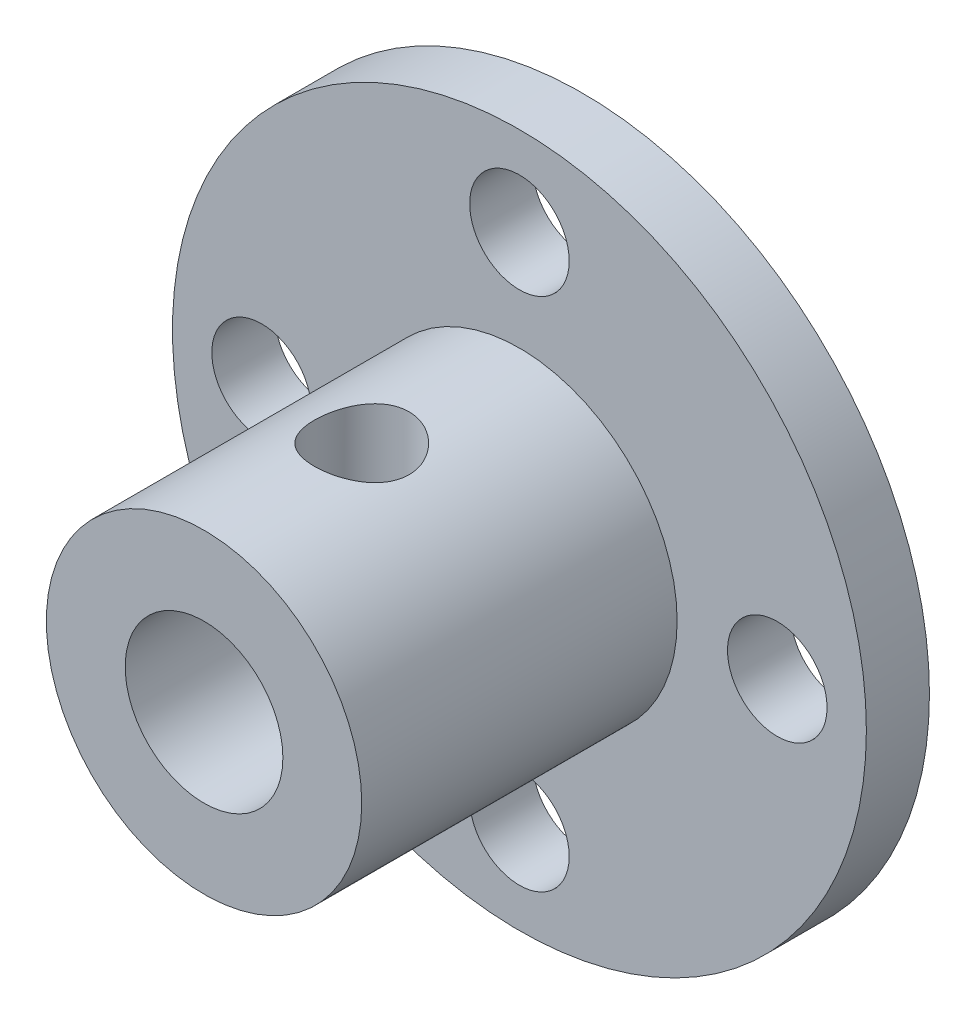
SolidWorks part; units mm, degrees
ref_plane "Front Plane" through (0, 0, 0) normal (0, 0, 1) x (1, 0, 0)
ref_plane "Top Plane" through (0, 0, 0) normal (0, 1, 0) x (1, 0, 0)
ref_plane "Right Plane" through (0, 0, 0) normal (1, 0, 0) x (0, 0, -1)
sketch "Sketch1" plane through (0, 0, 0) normal (0, 0, 1) x (1, 0, 0)
  line L0 (0, 0) -> (-6.6, 0) construction
  line L1 (-6.6, 0) -> (-9.75, 0) construction
  circle A0 centre (0, 0) radius 11
  circle A1 centre (0, 0) radius 2.5
  circle A2 centre (-8.175, 0) radius 1.5781
  circle A3 centre (0, 8.175) radius 1.5781
  circle A4 centre (8.175, 0) radius 1.5781
  circle A5 centre (0, -8.175) radius 1.5781
  point P17 (0, 0)
  dimension "D1" = 22
  dimension "D2" = 5
  dimension "D3" = 6.6
  dimension "D4" = 9.75
  dimension "D5" = 4
extrude "Boss-Extrude1" add sketch "Sketch1" along normal blind 2
sketch "Sketch2" plane through (0, 0, 2) normal (0, 0, 1) x (1, 0, 0)
  circle A0 centre (0, 0) radius 2.5
  circle A1 centre (0, 0) radius 5
  dimension "D1" = 10
extrude "Boss-Extrude2" add sketch "Sketch2" along normal blind 10
sketch "Sketch3" plane through (0, 0, 0) normal (0, 1, 0) x (1, 0, 0)
  line L0 (0, -2) -> (0, -12) construction
  line L1 (-5, -2) -> (5, -2) construction
  line L2 (-5, -12) -> (5, -12) construction
  circle A0 centre (0, -7) radius 1.5
  dimension "D1" = 3
extrude "Cut-Extrude1" cut sketch "Sketch3" against normal mid plane 21
